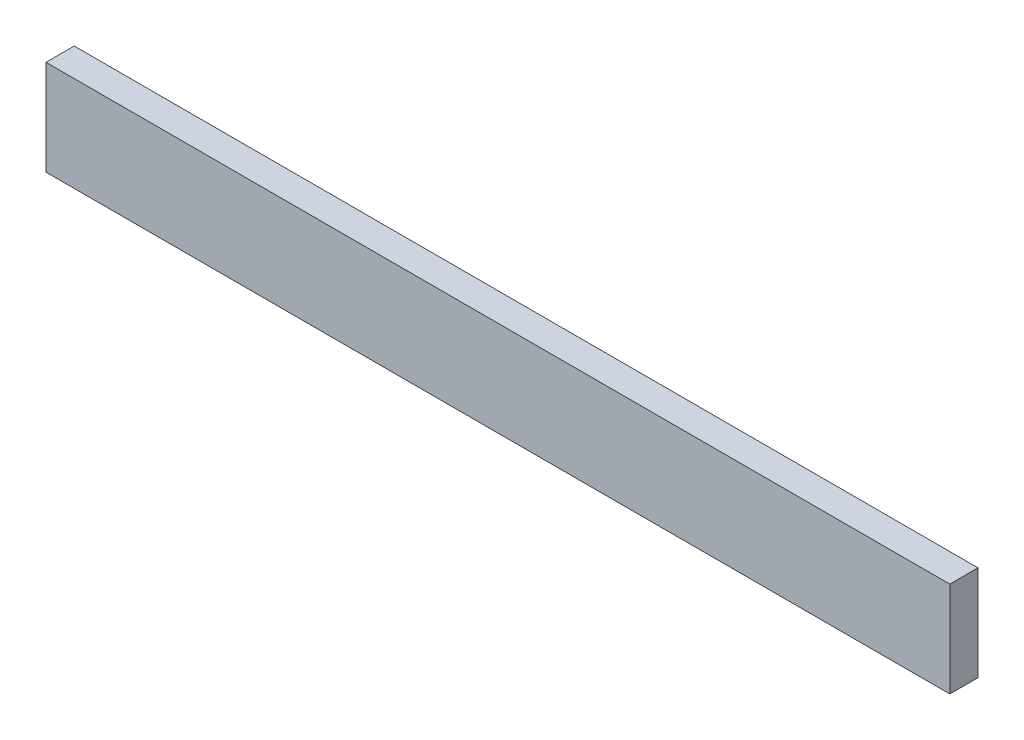
SolidWorks part; units mm, degrees
material "PF"
ref_plane "前视基准面" through (0, 0, 0) normal (0, 0, 1) x (1, 0, 0)
ref_plane "上视基准面" through (0, 0, 0) normal (0, 1, 0) x (1, 0, 0)
ref_plane "右视基准面" through (0, 0, 0) normal (1, 0, 0) x (0, 0, -1)
other "Configuration Table"
sketch "草图1" plane through (0, 0, 0) normal (0, 0, 1) x (1, 0, 0)
  line L1 (-140.9438, 78.513) -> (115.5115, 78.513)
  line L2 (-140.9438, 78.513) -> (-140.9438, 51.513)
  line L3 (-140.9438, 51.513) -> (115.5115, 51.513)
  line L4 (115.5115, 78.513) -> (115.5115, 51.513)
  dimension "D1" = 256.4553
  dimension "D2" = 27
extrude "凸台-拉伸1" add sketch "草图1" along normal blind 8
